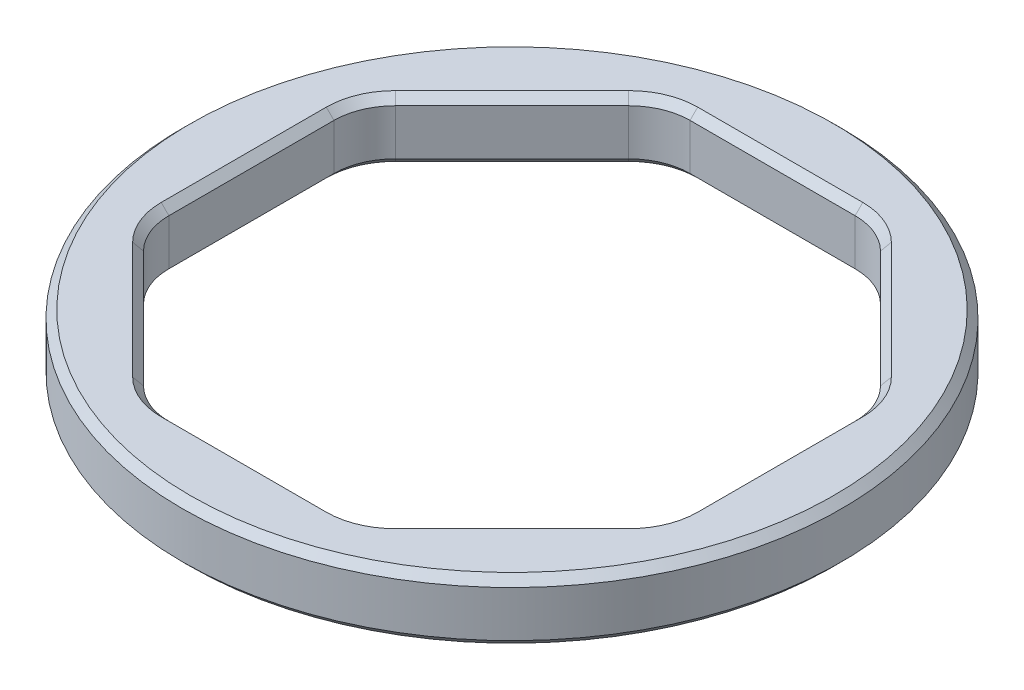
SolidWorks part; units mm, degrees
material "Plain Carbon Steel"
ref_plane "Front Plane" through (0, 0, 0) normal (0, 0, 1) x (1, 0, 0)
ref_plane "Top Plane" through (0, 0, 0) normal (0, 1, 0) x (1, 0, 0)
ref_plane "Right Plane" through (0, 0, 0) normal (1, 0, 0) x (0, 0, -1)
sketch "Sketch1" plane through (0, 0, 0) normal (0, 1, 0) x (1, 0, 0)
  line L1 (5.3848, 17) -> (-5.3848, 17)
  line L2 (-8.2132, 15.8284) -> (-15.8284, 8.2132)
  line L3 (-17, 5.3848) -> (-17, -5.3848)
  line L4 (-15.8284, -8.2132) -> (-8.2132, -15.8284)
  line L5 (-5.3848, -17) -> (5.3848, -17)
  line L6 (8.2132, -15.8284) -> (15.8284, -8.2132)
  line L7 (17, -5.3848) -> (17, 5.3848)
  line L8 (15.8284, 8.2132) -> (8.2132, 15.8284)
  circle A0 centre (0, 0) radius 21.5
  circle A1 centre (0, 0) radius 17 construction
  arc A2 (-5.3848, 17) -> (-8.2132, 15.8284) centre (-5.3848, 13) ccw
  arc A3 (5.3848, 17) -> (8.2132, 15.8284) centre (5.3848, 13) cw
  arc A4 (17, 5.3848) -> (15.8284, 8.2132) centre (13, 5.3848) ccw
  arc A5 (15.8284, -8.2132) -> (17, -5.3848) centre (13, -5.3848) ccw
  arc A6 (5.3848, -17) -> (8.2132, -15.8284) centre (5.3848, -13) ccw
  arc A7 (-8.2132, -15.8284) -> (-5.3848, -17) centre (-5.3848, -13) ccw
  arc A8 (-17, -5.3848) -> (-15.8284, -8.2132) centre (-13, -5.3848) ccw
  arc A9 (-15.8284, 8.2132) -> (-17, 5.3848) centre (-13, 5.3848) ccw
  dimension "D1" = 4
  dimension "D2" = 34
  dimension "D3" = 43
extrude "Boss-Extrude1" add sketch "Sketch1" along normal blind 4
chamfer "Chamfer1" distance 0.5 angle 45 34 edges at (-16.6955, 4, -6.9155) (-17, 4, 0) (-16.6955, 4, 6.9155) (-12.0208, 4, 12.0208) (-6.9155, 4, 16.6955) (0, 4, 17) (6.9155, 4, 16.6955) (12.0208, 4, 12.0208) (16.6955, 4, 6.9155) (17, 4, 0) (16.6955, 4, -6.9155) (12.0208, 4, -12.0208) (6.9155, 4, -16.6955) (0, 4, -17) (-6.9155, 4, -16.6955) (-12.0208, 4, -12.0208) (0, 0, -17) (6.9155, 0, -16.6955) (12.0208, 0, -12.0208) (16.6955, 0, -6.9155) (17, 0, 0) (16.6955, 0, 6.9155) (12.0208, 0, 12.0208) (6.9155, 0, 16.6955) (0, 0, 17) (-6.9155, 0, 16.6955) (-12.0208, 0, 12.0208) (-16.6955, 0, 6.9155) (-17, 0, 0) (-16.6955, 0, -6.9155) (-12.0208, 0, -12.0208) (-6.9155, 0, -16.6955) (0, 0, 21.5) (0, 4, 21.5)
